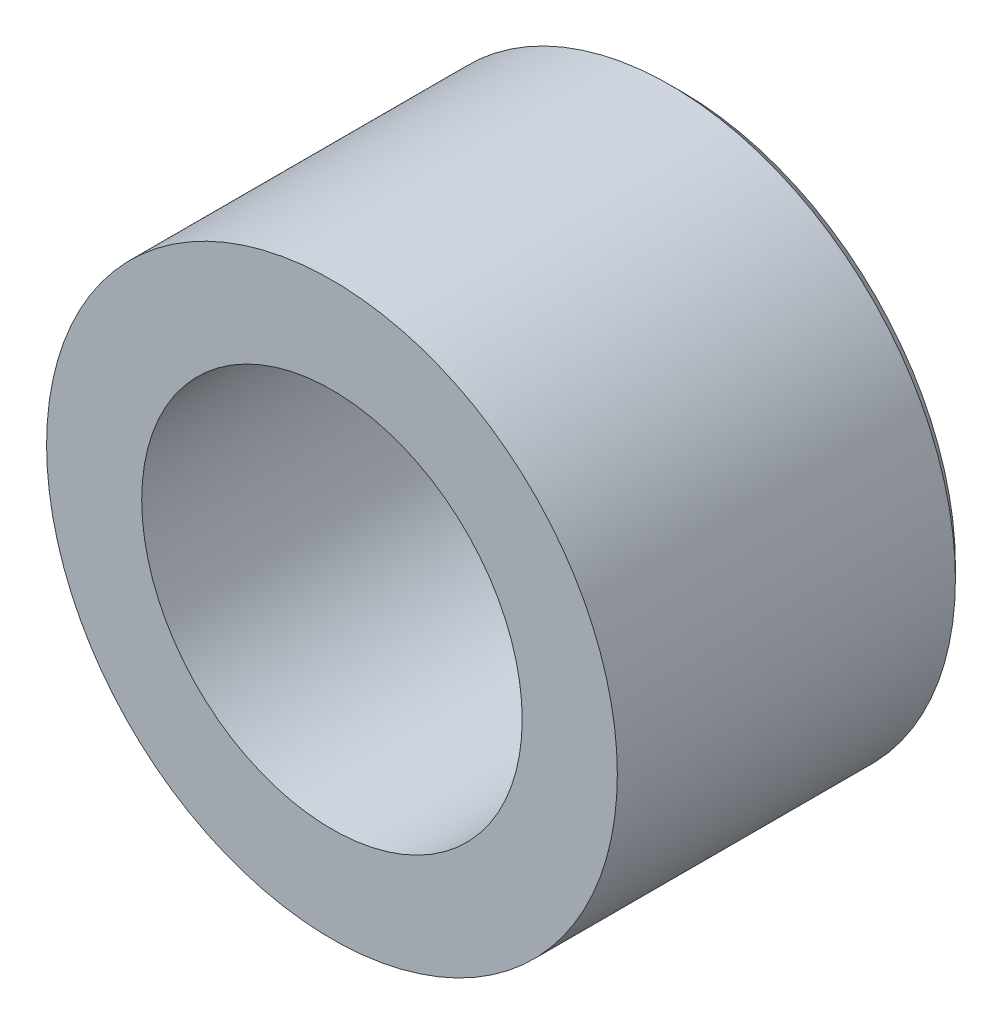
SolidWorks part; units mm, degrees
ref_plane "Front Plane" through (0, 0, 0) normal (0, 0, 1) x (1, 0, 0)
ref_plane "Top Plane" through (0, 0, 0) normal (0, 1, 0) x (1, 0, 0)
ref_plane "Right Plane" through (0, 0, 0) normal (1, 0, 0) x (0, 0, -1)
sketch "Sketch1" plane through (0, 0, 0) normal (0, 0, 1) x (1, 0, 0)
  circle A0 centre (0, 0) radius 3.175
  circle A1 centre (0, 0) radius 4.7625
  dimension "D1" = 6.35
  dimension "D2" = 9.525
extrude "Boss-Extrude1" add sketch "Sketch1" along normal blind 5.842
sketch "Sketch2" plane through (0, 0, 5.842) normal (0, 0, 1) x (1, 0, 0)
  circle A0 centre (0, 0) radius 3.175
  circle A1 centre (0, 0) radius 6.35
  dimension "D1" = 12.7
extrude "Boss-Extrude2" [suppressed] add sketch "Sketch2" along normal blind 3.175
chamfer "Chamfer1" distance 0.4 angle 45 1 edges at (3.175, 0, 0)
chamfer "Chamfer2" distance 0.2 angle 45 1 edges at (4.7625, 0, 0)
